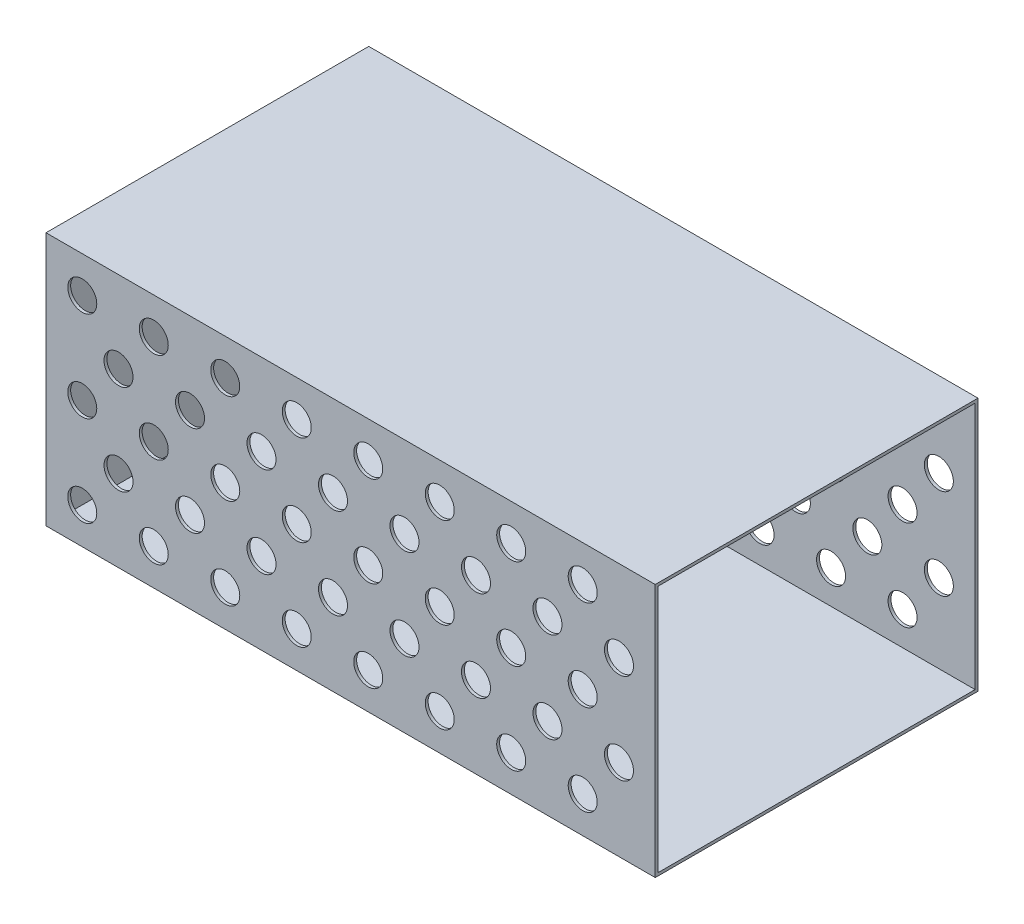
SolidWorks part; units mm, degrees
material "1060 Alloy"
ref_plane "Front Plane" through (0, 0, 0) normal (0, 0, 1) x (1, 0, 0)
ref_plane "Top Plane" through (0, 0, 0) normal (0, 1, 0) x (1, 0, 0)
ref_plane "Right Plane" through (0, 0, 0) normal (1, 0, 0) x (0, 0, -1)
sketch "Sketch1" plane through (0, 0, 0) normal (0, 1, 0) x (1, 0, 0)
  line L1 (84, -44.5) -> (-84, -44.5)
  line L2 (84, -44.5) -> (84, 44.5)
  line L3 (84, 44.5) -> (-84, 44.5)
  line L4 (-84, -44.5) -> (-84, 44.5)
  line L5 (84, -44.5) -> (-84, 44.5) construction
  line L6 (84, 44.5) -> (-84, -44.5) construction
  point P0 (0, 0)
  dimension "D1" = 89
  dimension "D2" = 168
extrude "Boss-Extrude1" add sketch "Sketch1" along normal blind 70
shell "Shell1" thickness 0.8
hole_wizard "Ø8.0mm Dowel Hole1" positions "Sketch3" profile "Sketch4" hole size "Ø8.0" standard "ANSI Metric" end condition through all
sketch "Sketch3" plane through (0, 0, 44.5) normal (0, 0, 1) x (1, 0, 0)
  line L0 (-84, 35) -> (84, 35) construction
  line L1 (-84, 70) -> (-84, 0) construction
  line L2 (84, 70) -> (84, 0) construction
  line L4 (-84, 60) -> (84, 60) construction
  line L6 (-84, 47.5) -> (84, 47.5) construction
  line L8 (-84, 10) -> (84, 10) construction
  line L10 (-84, 22.5) -> (84, 22.5) construction
  line L11 (-74, 60) -> (-74, 10) construction
  line L13 (-64, 47.5) -> (-64, 22.5) construction
  line L15 (-54.2857, 60) -> (-54.2857, 10) construction
  line L16 (-34.5714, 60) -> (-34.5714, 10) construction
  line L17 (-14.8571, 60) -> (-14.8571, 10) construction
  line L18 (4.8571, 60) -> (4.8571, 10) construction
  line L19 (24.5714, 60) -> (24.5714, 10) construction
  line L20 (44.2857, 60) -> (44.2857, 10) construction
  line L21 (64, 60) -> (64, 10) construction
  point P24 (-74, 60)
  point P26 (-64, 47.5)
  point P28 (-74, 35)
  point P30 (-64, 22.5)
  point P32 (-74, 10)
  point P52 (-54.2857, 60)
  point P53 (-44.2857, 47.5)
  point P54 (-54.2857, 35)
  point P55 (-44.2857, 22.5)
  point P56 (-54.2857, 10)
  point P59 (-34.5714, 60)
  point P60 (-24.5714, 47.5)
  point P61 (-34.5714, 35)
  point P62 (-24.5714, 22.5)
  point P63 (-34.5714, 10)
  point P66 (-14.8571, 60)
  point P67 (-4.8571, 47.5)
  point P68 (-14.8571, 35)
  point P69 (-4.8571, 22.5)
  point P70 (-14.8571, 10)
  point P73 (4.8571, 60)
  point P74 (14.8571, 47.5)
  point P75 (4.8571, 35)
  point P76 (14.8571, 22.5)
  point P77 (4.8571, 10)
  point P80 (24.5714, 60)
  point P81 (34.5714, 47.5)
  point P82 (24.5714, 35)
  point P83 (34.5714, 22.5)
  point P84 (24.5714, 10)
  point P87 (44.2857, 60)
  point P88 (54.2857, 47.5)
  point P89 (44.2857, 35)
  point P90 (54.2857, 22.5)
  point P91 (44.2857, 10)
  point P94 (64, 60)
  point P95 (74, 47.5)
  point P96 (64, 35)
  point P97 (74, 22.5)
  point P98 (64, 10)
  dimension "D1" = 25
  dimension "D2" = 12.5
  dimension "D3" = 12.5
  dimension "D4" = 25
  dimension "D5" = 10
  dimension "D6" = 10
  dimension "D8" = 10
  dimension "D7" = 8
sketch "Sketch4" plane through (64, 10, 44.5) normal (1, 0, 0) x (0, -1, 0)
  line L0 (0, 0) -> (0, 89)
  line L1 (0, 89) -> (4, 89)
  line L2 (4, 89) -> (4, 0)
  line L5 (4, 0) -> (0, 0)
  line L11 (0, -6.35) -> (0, 107.95) construction
  dimension "Thru Hole Dia." = 8
  dimension "Thru Hole Depth" = 89
